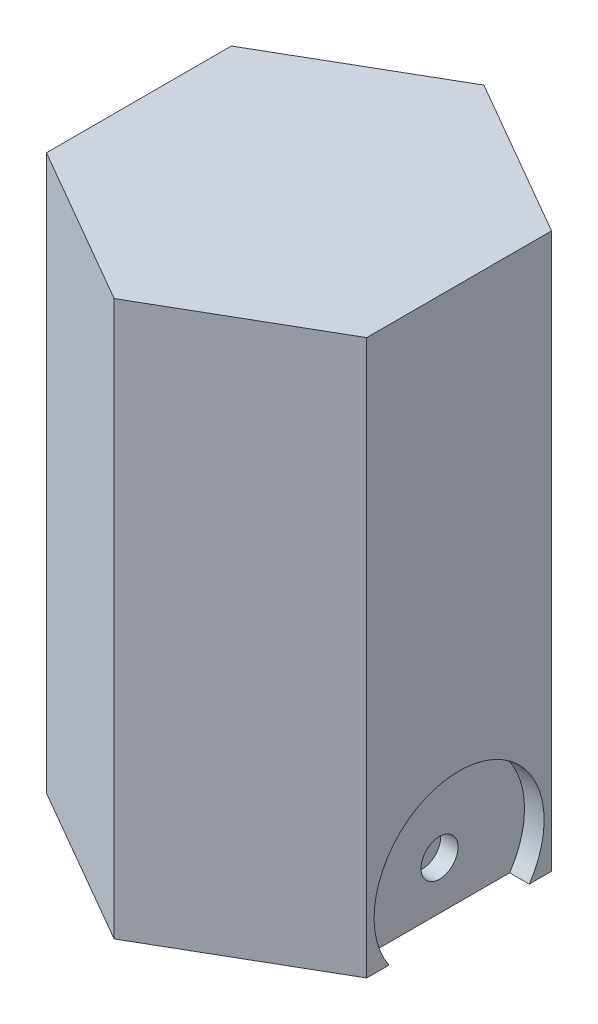
SolidWorks part; units mm, degrees
material "1060 Alloy"
ref_plane "Front Plane" through (0, 0, 0) normal (0, 0, 1) x (1, 0, 0)
ref_plane "Top Plane" through (0, 0, 0) normal (0, 1, 0) x (1, 0, 0)
ref_plane "Right Plane" through (0, 0, 0) normal (1, 0, 0) x (0, 0, -1)
sketch "Sketch1" plane through (0, 0, 0) normal (0, 1, 0) x (1, 0, 0)
  line L1 (0, 50) -> (-43.3013, 25)
  line L2 (-43.3013, 25) -> (-43.3013, -25)
  line L3 (-43.3013, -25) -> (0, -50)
  line L4 (0, -50) -> (43.3013, -25)
  line L5 (43.3013, -25) -> (43.3013, 25)
  line L6 (43.3013, 25) -> (0, 50)
  circle A0 centre (0, 0) radius 43.3013 construction
  dimension "D1" = 50
extrude "Boss-Extrude1" add sketch "Sketch1" along normal blind 150 from offset 10
sketch "Sketch3" plane through (0, 0, 0) normal (1, 0, 0) x (0, 0, -1)
  circle A0 centre (0, 23) radius 23
  dimension "D1" = 46
extrude "Cut-Extrude1" cut sketch "Sketch3" against normal up to surface (81.3013 mm away) from offset 38 offset against normal yes
sketch "Sketch4" plane through (0, 0, 0) normal (1, 0, 0) x (0, 0, -1)
  arc A0 (18.9737, 10) -> (-18.9737, 10) centre (0, 23) ccw construction
  arc A1 (18.9737, 10) -> (-18.9737, 10) centre (0, 23) ccw construction
  circle A2 centre (0, 23) radius 5
  dimension "D1" = 10
extrude "Cut-Extrude2" cut sketch "Sketch4" against normal up to surface (4.7 mm away) from offset 33.3 up to face at (-38, 28, 0) offset against normal yes
mirror "Mirror4" about plane through (0, 0, 0) normal (1, 0, 0) of "Cut-Extrude2", "Cut-Extrude1"
